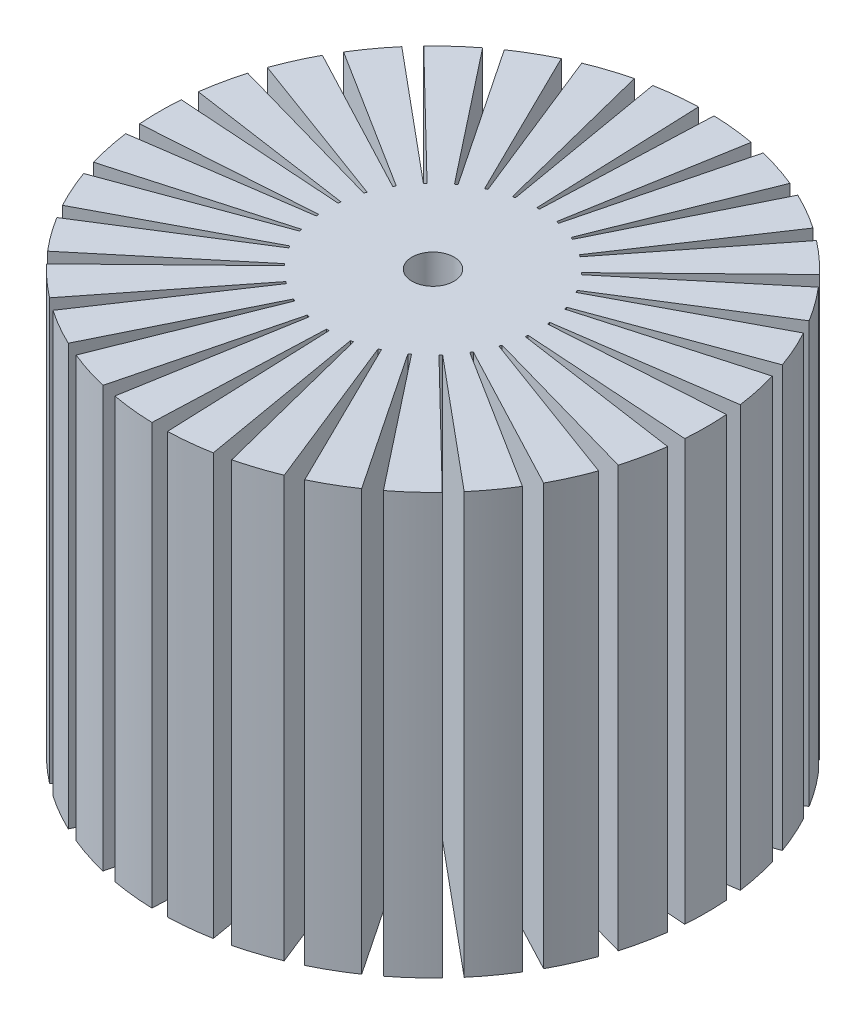
SolidWorks part; units mm, degrees
ref_plane "Front Plane" through (0, 0, 0) normal (0, 0, 1) x (1, 0, 0)
ref_plane "Top Plane" through (0, 0, 0) normal (0, 1, 0) x (1, 0, 0)
ref_plane "Right Plane" through (0, 0, 0) normal (1, 0, 0) x (0, 0, -1)
sketch "Sketch1" plane through (0, 0, 0) normal (0, 1, 0) x (1, 0, 0)
  circle A0 centre (0, 0) radius 32.5
  dimension "D1" = 65
extrude "Boss-Extrude1" add sketch "Sketch1" along normal blind 50
sketch "Sketch2" plane through (0, 50, 0) normal (0, 1, 0) x (1, 0, 0)
  line L0 (-0.9231, 32.4869) -> (-0.1539, 12.5)
  line L1 (0.1539, 12.5) -> (0.9231, 32.4869)
  line L2 (0.1539, 12.5) -> (-0.1539, 12.5)
  circle A0 centre (0, 0) radius 32.5 construction
  dimension "D1" = 20
extrude "Cut-Extrude1" cut sketch "Sketch2" against normal through all both and the other way through all
pattern_circular "CirPattern1" count 30 over 360 about axis through (0, 50, 0) along (0, 1, 0) of "Cut-Extrude1"
sketch "Sketch3" plane through (0, 50, 0) normal (0, 1, 0) x (1, 0, 0)
  circle A0 centre (0, 0) radius 2.5
  dimension "D1" = 5
extrude "Cut-Extrude2" cut sketch "Sketch3" against normal through all both and the other way through all
